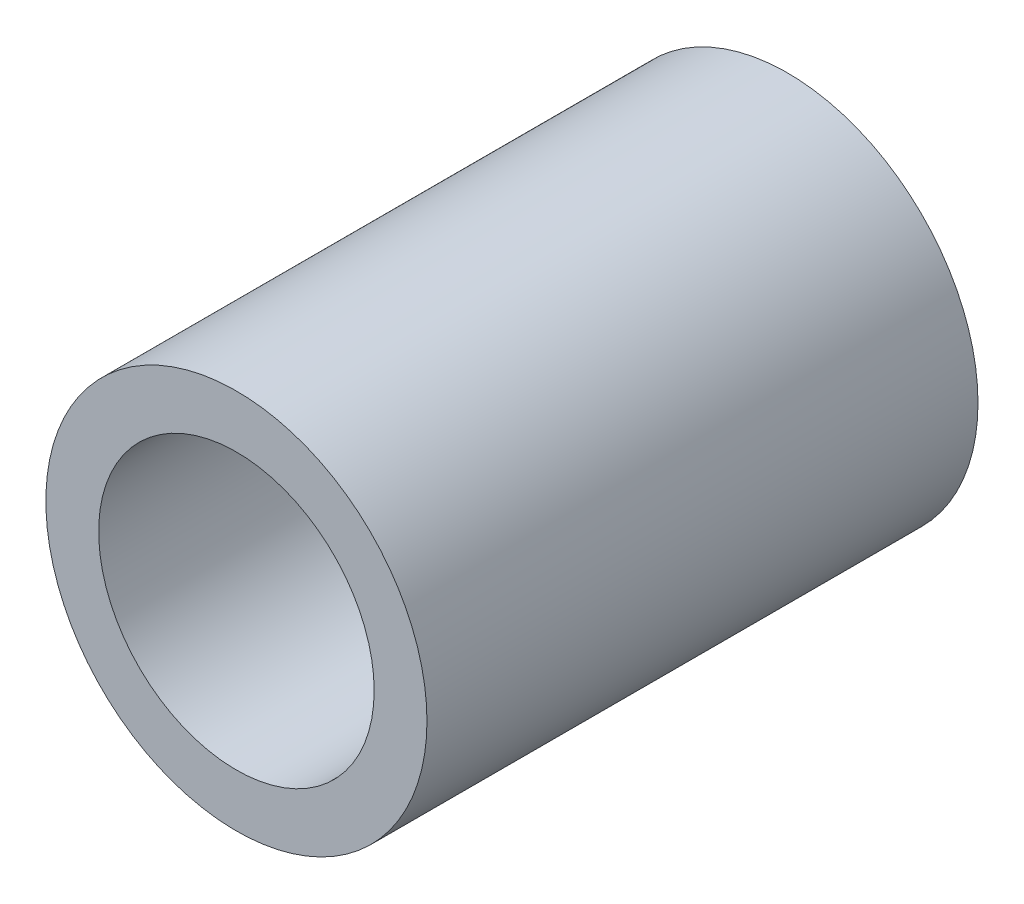
SolidWorks part; units mm, degrees
material "AISI 304"
ref_plane "Plan de face" through (0, 0, 0) normal (0, 0, 1) x (1, 0, 0)
ref_plane "Plan de dessus" through (0, 0, 0) normal (0, 1, 0) x (1, 0, 0)
ref_plane "Plan de droite" through (0, 0, 0) normal (1, 0, 0) x (0, 0, -1)
sketch "Esquisse1" plane through (0, 0, 0) normal (0, 0, 1) x (1, 0, 0)
  circle A0 centre (0, 0) radius 30
  circle A1 centre (0, 0) radius 41.5
  dimension "D1" = 60
  dimension "D2" = 83
extrude "Extrusion1" add sketch "Esquisse1" along normal blind 120
